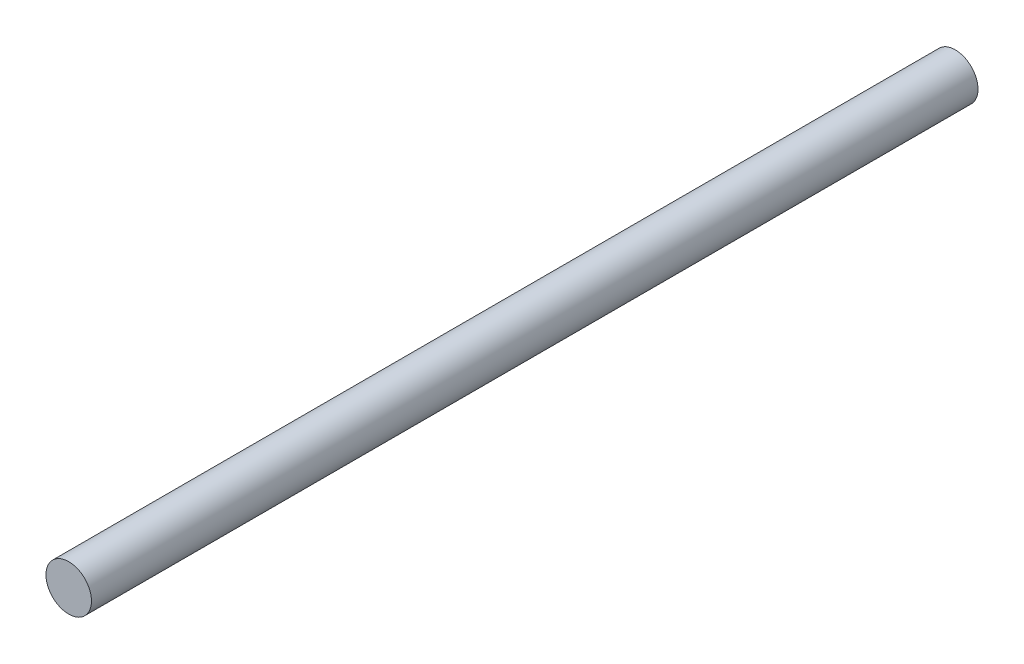
SolidWorks part; units mm, degrees
ref_plane "Plano frontal" through (0, 0, 0) normal (0, 0, 1) x (1, 0, 0)
ref_plane "Plano superior" through (0, 0, 0) normal (0, 1, 0) x (1, 0, 0)
ref_plane "Plano direito" through (0, 0, 0) normal (1, 0, 0) x (0, 0, -1)
sketch "Esboço1" plane through (0, 0, 0) normal (0, 0, 1) x (1, 0, 0)
  circle A0 centre (0, 0) radius 1.35
extrude "Ressalto-extrusão1" add sketch "Esboço1" along normal blind 52.6
